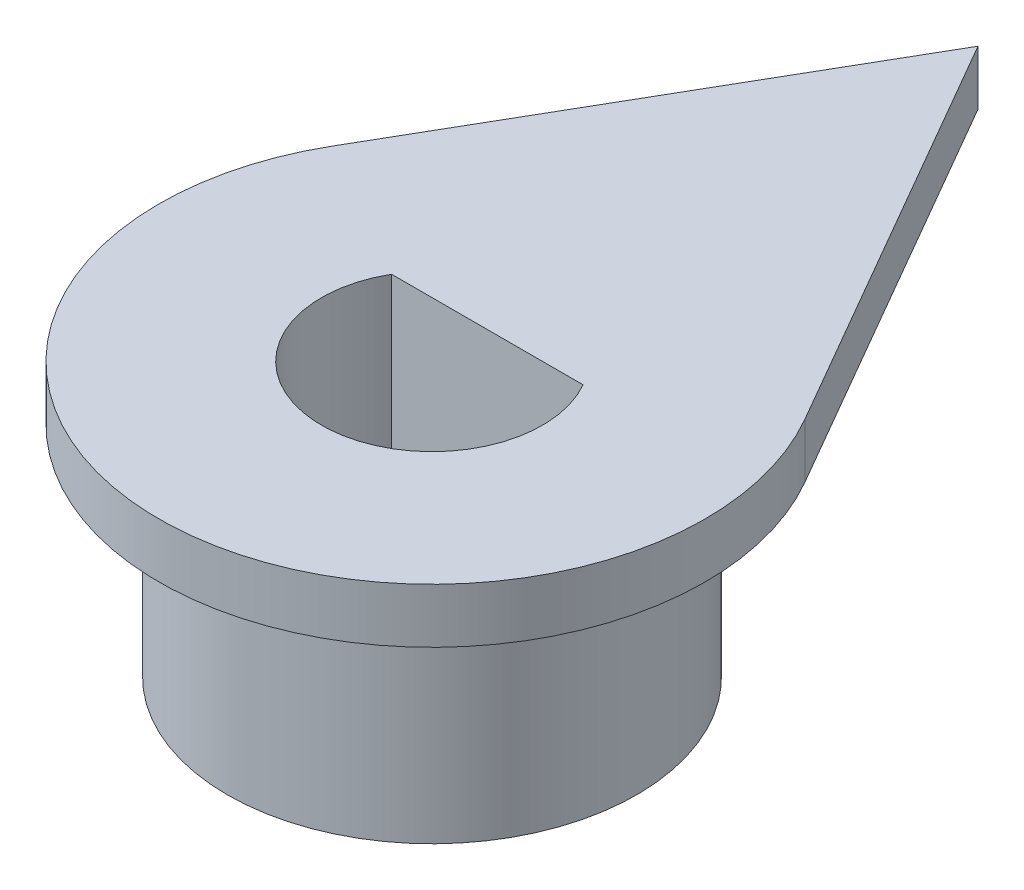
SolidWorks part; units mm, degrees
ref_plane "前视基准面" through (0, 0, 0) normal (0, 0, 1) x (1, 0, 0)
ref_plane "上视基准面" through (0, 0, 0) normal (0, 1, 0) x (1, 0, 0)
ref_plane "右视基准面" through (0, 0, 0) normal (1, 0, 0) x (0, 0, -1)
sketch "草图1" plane through (0, 0, 0) normal (0, 1, 0) x (1, 0, 0)
  circle A0 centre (0, 0) radius 4.05
  circle A1 centre (0, 0) radius 7.5
  dimension "D1" = 8.1
  dimension "D2" = 15
extrude "凸台-拉伸1" add sketch "草图1" along normal blind 10
sketch "草图2" plane through (0, 10, 0) normal (0, 1, 0) x (1, 0, 0)
  line L0 (0, 0) -> (0, 21.1609) construction
  line L1 (-13.4376, 5) -> (12.3669, 5) construction
  line L2 (0, 0) -> (-8.6603, 5) construction
  line L3 (0, 0) -> (8.6603, 5) construction
  line L4 (-8.6603, 5) -> (0, 20)
  line L5 (0, 20) -> (8.6603, 5)
  arc A0 (-8.6603, 5) -> (8.6603, 5) centre (0, 0) ccw
  circle A1 centre (0, 0) radius 4.05 construction
  circle A2 centre (0, 0) radius 4.05
  dimension "D1" = 20
  dimension "D2" = 120
extrude "凸台-拉伸2" add sketch "草图2" against normal blind 2
sketch "草图3" plane through (0, 0, 0) normal (0, -1, 0) x (1, 0, 0)
  line L0 (-3.5074, -2.025) -> (3.5074, -2.025) construction
  line L1 (3.5074, -2.025) -> (0, 0) construction
  line L2 (0, 0) -> (-3.5074, -2.025) construction
  line L3 (-3.5074, -2.025) -> (3.5074, -2.025)
  circle A0 centre (0, 0) radius 4.05 construction
  arc A1 (-3.5074, -2.025) -> (3.5074, -2.025) centre (0, 0) ccw
  dimension "D1" = 120
extrude "凸台-拉伸3" add sketch "草图3" against normal blind 10
sketch "草图4" plane through (0, 0, 0) normal (0, 0, 1) x (1, 0, 0)
  line L0 (0, 0) -> (0, 3.5) construction
  line L1 (-7.5, 0) -> (7.5, 0) construction
  circle A0 centre (0, 3.5) radius 1.45
  dimension "D1" = 2.9
  dimension "D2" = 3.5
extrude "切除-拉伸1" cut sketch "草图4" against normal blind 10
